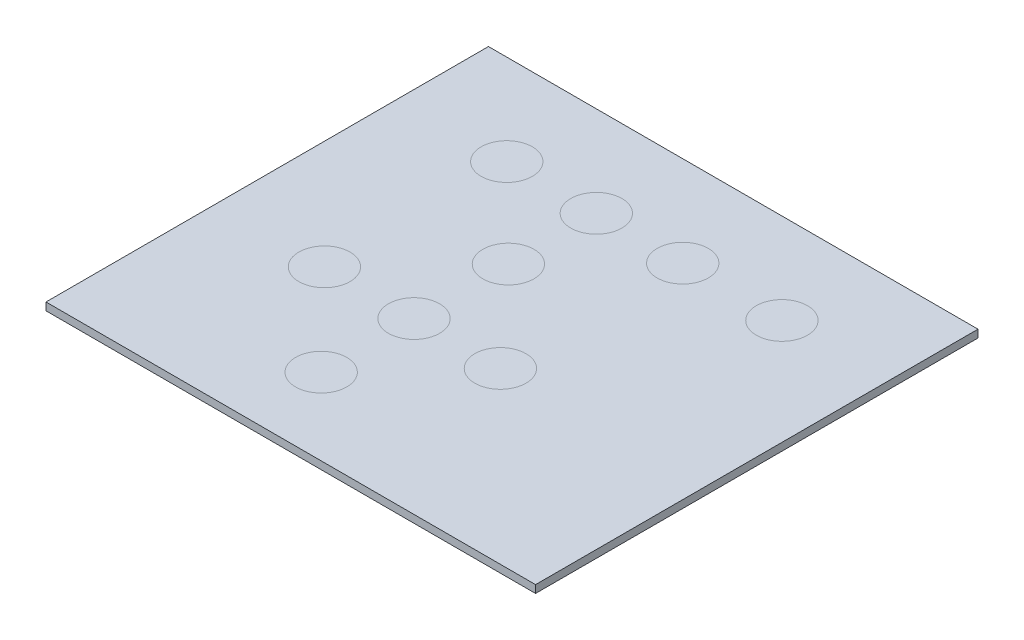
SolidWorks part; units mm, degrees
ref_plane "Front" through (0, 0, 0) normal (0, 0, 1) x (1, 0, 0)
ref_plane "Top" through (0, 0, 0) normal (0, 1, 0) x (1, 0, 0)
ref_plane "Right" through (0, 0, 0) normal (1, 0, 0) x (0, 0, -1)
sketch "Sketch1" plane through (0, 0, 0) normal (0, 1, 0) x (1, 0, 0)
  line L1 (38.25, 34.57) -> (-38.25, 34.57)
  line L2 (38.25, 34.57) -> (38.25, -34.57)
  line L3 (38.25, -34.57) -> (-38.25, -34.57)
  line L4 (-38.25, 34.57) -> (-38.25, -34.57)
  line L5 (38.25, 34.57) -> (-38.25, -34.57) construction
  line L6 (38.25, -34.57) -> (-38.25, 34.57) construction
  point P0 (0, 0)
  dimension "D1" = 69.14
  dimension "D2" = 76.5
extrude "Boss-Extrude1" add sketch "Sketch1" along normal blind 1.2
sketch "Sketch2" plane through (0, 1.2, 0) normal (0, 1, 0) x (1, 0, 0)
  line L0 (-21.25, 34.57) -> (-21.25, -34.57) construction
  line L1 (38.25, 34.57) -> (-38.25, 34.57) construction
  line L2 (-38.25, -34.57) -> (38.25, -34.57) construction
  line L3 (6.25, 34.57) -> (6.25, -34.57) construction
  line L4 (-7.25, 34.57) -> (-7.25, -34.57) construction
  line L5 (-7.25, -34.57) -> (-11.5134, -38.8334) construction
  line L6 (-38.25, 34.57) -> (-38.25, -34.57) construction
  line L7 (-38.25, -22.57) -> (38.25, -22.57) construction
  line L8 (38.25, -34.57) -> (38.25, 34.57) construction
  line L9 (-38.25, -8.06) -> (38.25, -8.06) construction
  line L10 (38.25, 6.69) -> (-38.25, 6.69) construction
  line L11 (-38.25, 20.43) -> (38.25, 20.43) construction
  line L12 (21.75, 34.57) -> (21.75, 20.43) construction
  circle A0 centre (-21.25, -8.06) radius 4
  circle A1 centre (-21.25, 20.43) radius 4
  circle A2 centre (-7.25, 20.43) radius 4
  circle A3 centre (6.25, 20.43) radius 4
  circle A4 centre (21.75, 20.43) radius 4
  circle A5 centre (6.25, -8.06) radius 4
  circle A6 centre (-7.25, -8.06) radius 4
  circle A7 centre (-7.25, -22.57) radius 4
  circle A8 centre (-7.25, 6.69) radius 4
  dimension "D9" = 8
  dimension "D1" = 17
  dimension "D2" = 31
  dimension "D3" = 44.5
  dimension "D4" = 12
  dimension "D5" = 26.51
  dimension "D6" = 41.26
  dimension "D7" = 55
  dimension "D8" = 60
split line "Split Line1"
